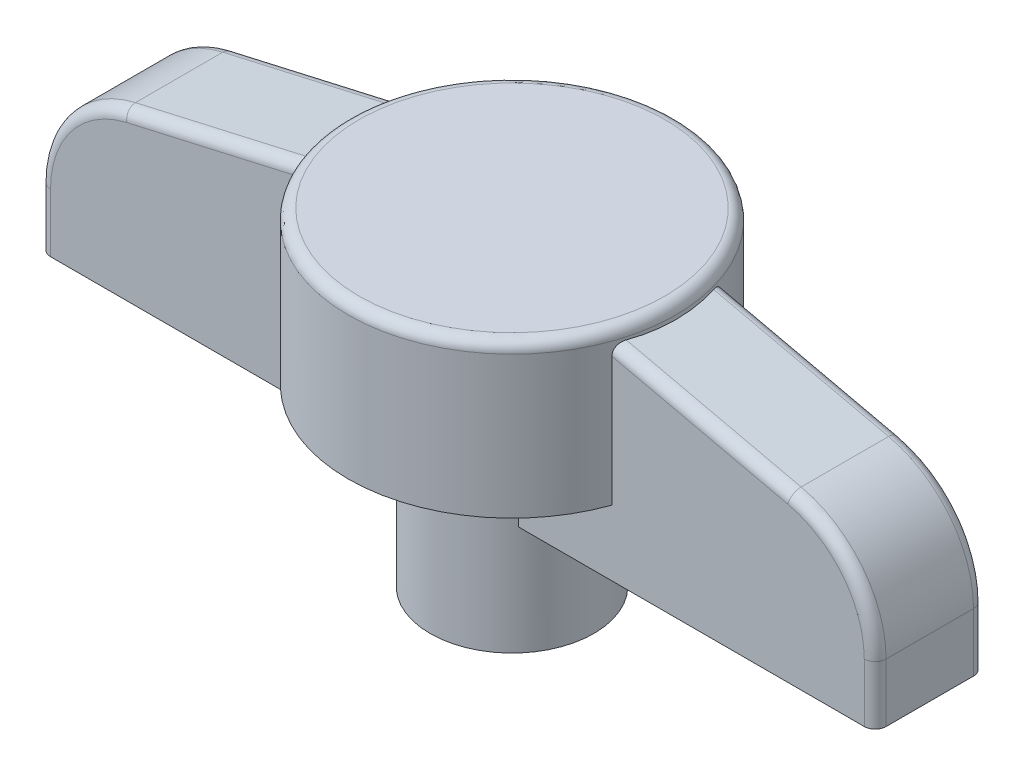
SolidWorks part; units mm, degrees
material "PVC rigide"
ref_plane "Plan de face" through (0, 0, 0) normal (0, 0, 1) x (1, 0, 0)
ref_plane "Plan de dessus" through (0, 0, 0) normal (0, 1, 0) x (1, 0, 0)
ref_plane "Plan de droite" through (0, 0, 0) normal (1, 0, 0) x (0, 0, -1)
sketch "Esquisse1" plane through (0, 0, 0) normal (0, 0, 1) x (1, 0, 0)
  line L0 (38.25, 0) -> (-38.25, 0)
  line L1 (-38.25, 0) -> (-38.25, 5.3565)
  line L2 (-30.472, 15.1065) -> (-9, 20)
  line L3 (-9, 20) -> (9, 20)
  line L5 (0, 49.4901) -> (0, -26.3388) construction
  line L8 (0, 20) -> (0, 0)
  line L9 (30.472, 15.1065) -> (9, 20)
  line L10 (38.25, 0) -> (38.25, 5.3565)
  arc A0 (-38.25, 5.3565) -> (-30.472, 15.1065) centre (-28.25, 5.3565) cw
  arc A1 (38.25, 5.3565) -> (30.472, 15.1065) centre (28.25, 5.3565) ccw
  point P16 (-38.25, 13.3339)
  dimension "D5" = 10
  dimension "D1" = 38.25
  dimension "D2" = 9
  dimension "D3" = 20
  dimension "D4" = 30
extrude "Boss.-Extru.1" add sketch "Esquisse1" along normal blind 10 contours A0 L1 L0 L8 L3 L2 | L10 A1 L9 L3 L8 L0
sketch "Esquisse2" plane through (0, 20, 0) normal (0, 1, 0) x (1, 0, 0)
  line L0 (-38.25, -5) -> (38.25, -5) construction
  line L1 (-38.25, -10) -> (-38.25, 0) construction
  line L2 (38.25, -10) -> (38.25, 0) construction
  circle A0 centre (0, -5) radius 7.5
  dimension "D1" = 15
extrude "Boss.-Extru.2" add sketch "Esquisse2" against normal blind 30
fillet "Congé1" radius 1 16 edges at (-38.25, 2.6782, 10) (-7.2951, 20, 0) (19.736, 17.5532, 0) (36.0673, 11.5926, 0) (38.25, 2.6782, 0) (-38.25, 2.6782, 0) (-36.0673, 11.5926, 0) (38.25, 2.6782, 10) (36.0673, 11.5926, 10) (7.2951, 20, 0) (7.2951, 20, 10) (19.736, 17.5532, 10) (-7.2951, 20, 10) (-19.736, 17.5532, 10) (-36.0673, 11.5926, 10) (-19.736, 17.5532, 0)
sketch "Esquisse3" plane through (0, 20, 0) normal (0, 1, 0) x (1, 0, 0)
  circle A0 centre (0, -5) radius 15
  dimension "D1" = 30
extrude "Boss.-Extru.3" add sketch "Esquisse3" against normal blind 14
fillet "Congé2" radius 1 1 edges at (0, 20, 20)
